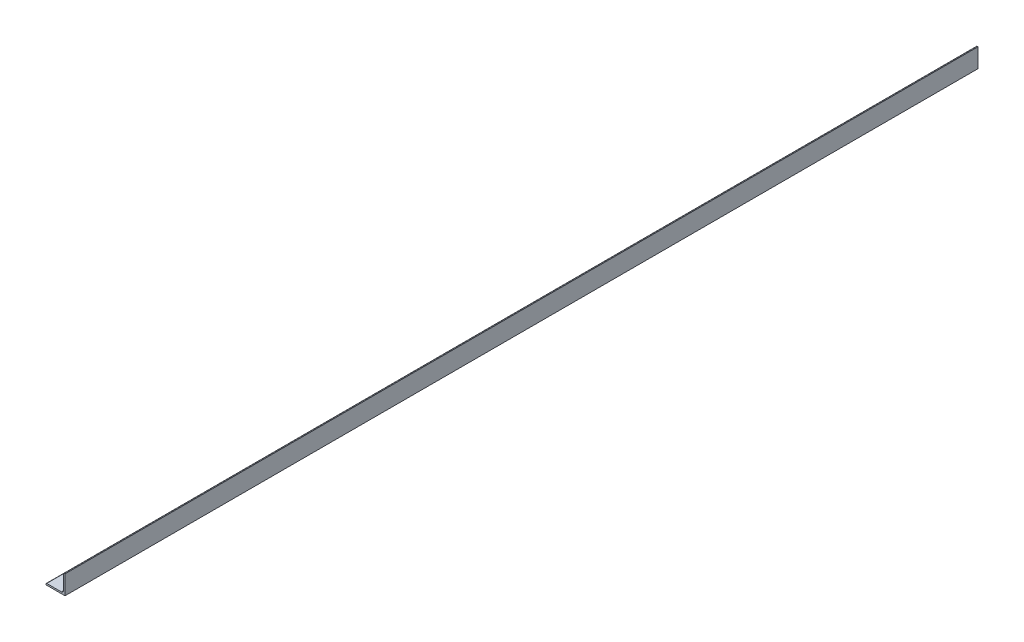
SolidWorks part; units mm, degrees
ref_plane "Front Plane" through (0, 0, 0) normal (0, 0, 1) x (1, 0, 0)
ref_plane "Top Plane" through (0, 0, 0) normal (0, 1, 0) x (1, 0, 0)
ref_plane "Right Plane" through (0, 0, 0) normal (1, 0, 0) x (0, 0, -1)
sketch "Sketch0" plane through (0, 0, 0) normal (0, 0, 1) x (1, 0, 0)
  line L0 (-9.525, -9.525) -> (9.525, -9.525)
  line L1 (9.525, -9.525) -> (9.525, 9.525)
  line L2 (9.525, 0) -> (0, 0) construction
  line L3 (0, 0) -> (0, -9.525) construction
  line L4 (7.9375, -5.5499) -> (7.9375, 9.525) construction
  line L5 (5.5499, -7.9375) -> (-9.525, -7.9375) construction
  arc A0 (7.9375, -5.5499) -> (5.5499, -7.9375) centre (5.5499, -5.5499) cw
  point P3 (7.2382, -7.2382)
  dimension "Inside Corner Radius" = 2.3876
  dimension "Outside Height" = 19.05
  dimension "Inside Height" = 17.4625
  dimension "Inside Width" = 17.4625
  dimension "Wall Thickness" = 1.5875
  dimension "D1" = 1.5875
  dimension "Outside Width" = 19.05
sketch "Sketch1" plane through (0, 0, 0) normal (1, 0, 0) x (0, 0, -1)
  line L0 (457.2, 0) -> (-457.2, 0)
  point P4 (0, 0)
  dimension "Length" = 914.4
sketch "Sketch2" plane through (0, 0, 0) normal (0, 0, 1) x (1, 0, 0)
  line L0 (-9.525, -9.525) -> (9.525, -9.525)
  line L1 (9.525, -9.525) -> (9.525, 9.525)
  line L2 (9.525, 9.525) -> (7.9375, 9.525) construction
  line L3 (7.9375, 8.7313) -> (7.9375, -5.5499)
  line L4 (5.5499, -7.9375) -> (-8.7313, -7.9375)
  line L5 (-9.525, -9.525) -> (-9.525, -7.9375) construction
  line L6 (8.7313, 9.525) -> (9.525, 9.525)
  line L7 (-9.525, -8.7313) -> (-9.525, -9.525)
  line L8 (9.525, 0) -> (0, 0) construction
  line L9 (0, 0) -> (0, -9.525) construction
  arc A0 (7.9375, 8.7313) -> (8.7313, 9.525) centre (8.7313, 8.7313) cw
  arc A1 (-9.525, -8.7313) -> (-8.7313, -7.9375) centre (-8.7313, -8.7313) cw
  arc A2 (7.9375, -5.5499) -> (5.5499, -7.9375) centre (5.5499, -5.5499) cw
  dimension "Inside Radius" = 2.3876
  dimension "Height" = 19.05
  dimension "Width" = 19.05
  dimension "Thickness" = 1.5875
extrude "Boss-Extrude1" add sketch "Sketch2" along normal mid plane 914.4
sketch "Break Locations" plane through (0, 0, 0) normal (1, 0, 0) x (0, 0, -1)
  line L0 (-437.769, 0) -> (437.769, 0)
  line L1 (-457.2, -9.525) -> (-457.2, 9.525) construction
  line L2 (457.2, -9.525) -> (457.2, 9.525) construction
  point P0 (-441.0075, 0)
  point P1 (441.0075, 0)
  point P10 (0, 0)
  point P11 (437.769, 0)
  point P13 (-437.769, 0)
  dimension "D1" = 16.1925
  dimension "D2" = 16.1925
  dimension "D3" = 19.431
equation "\"D1@Break Locations\" = .85 * \"Height@Sketch2\""
equation "\"D2@Break Locations\"=\"D1@Break Locations\""
equation "\"Thickness@Sketch2\"=\"wall thickness@sketch0\""
equation "\"Height@Sketch2\"=\"outside height@sketch0\""
equation "\"Width@Sketch2\"=\"outside width@sketch0\""
equation "\"Inside Radius@Sketch2\"=\"inside corner radius@sketch0\""
equation "\"Length@Boss-Extrude1\"=\"length@sketch1\""
equation "\"D3@Break Locations\"=\"D2@Break Locations\"*1.2"
equation "\"D1@Sketch0\"=\"Wall Thickness@Sketch0\""
